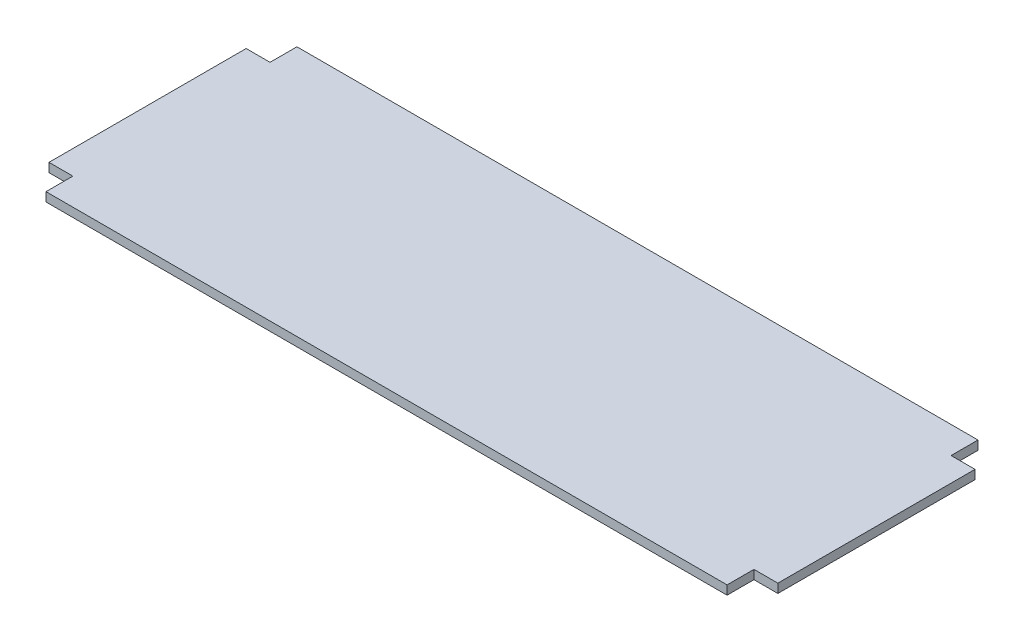
SolidWorks part; units mm, degrees
ref_plane "Plano frontal" through (0, 0, 0) normal (0, 0, 1) x (1, 0, 0)
ref_plane "Plano superior" through (0, 0, 0) normal (0, 1, 0) x (1, 0, 0)
ref_plane "Plano direito" through (0, 0, 0) normal (1, 0, 0) x (0, 0, -1)
sketch "Esboço1" plane through (0, 0, 0) normal (0, 1, 0) x (1, 0, 0)
  line L1 (610, -210) -> (-610, -210)
  line L2 (610, -210) -> (610, 210)
  line L3 (610, 210) -> (-610, 210)
  line L4 (-610, -210) -> (-610, 210)
  line L5 (610, -210) -> (-610, 210) construction
  line L6 (610, 210) -> (-610, -210) construction
  point P0 (0, 0)
  dimension "D1" = 1220
  dimension "D2" = 420
extrude "Ressalto-extrusão1" add sketch "Esboço1" along normal blind 15
sketch "Esboço2" plane through (0, 15, 0) normal (0, 1, 0) x (1, 0, 0)
  line L1 (-610, 210) -> (-570, 210)
  line L2 (-610, 210) -> (-610, 165)
  line L3 (-610, 165) -> (-570, 165)
  line L4 (-570, 210) -> (-570, 165)
  line L5 (-610, -210) -> (-570, -210)
  line L6 (-610, -210) -> (-610, -165)
  line L7 (-610, -165) -> (-570, -165)
  line L8 (-570, -210) -> (-570, -165)
  line L9 (610, -210) -> (570, -210)
  line L10 (610, -210) -> (610, -165)
  line L11 (610, -165) -> (570, -165)
  line L12 (570, -210) -> (570, -165)
  line L13 (610, 210) -> (570, 210)
  line L14 (610, 210) -> (610, 165)
  line L15 (610, 165) -> (570, 165)
  line L16 (570, 210) -> (570, 165)
  dimension "D1" = 45
  dimension "D2" = 40
extrude "Corte-extrusão1" cut sketch "Esboço2" against normal blind 15
